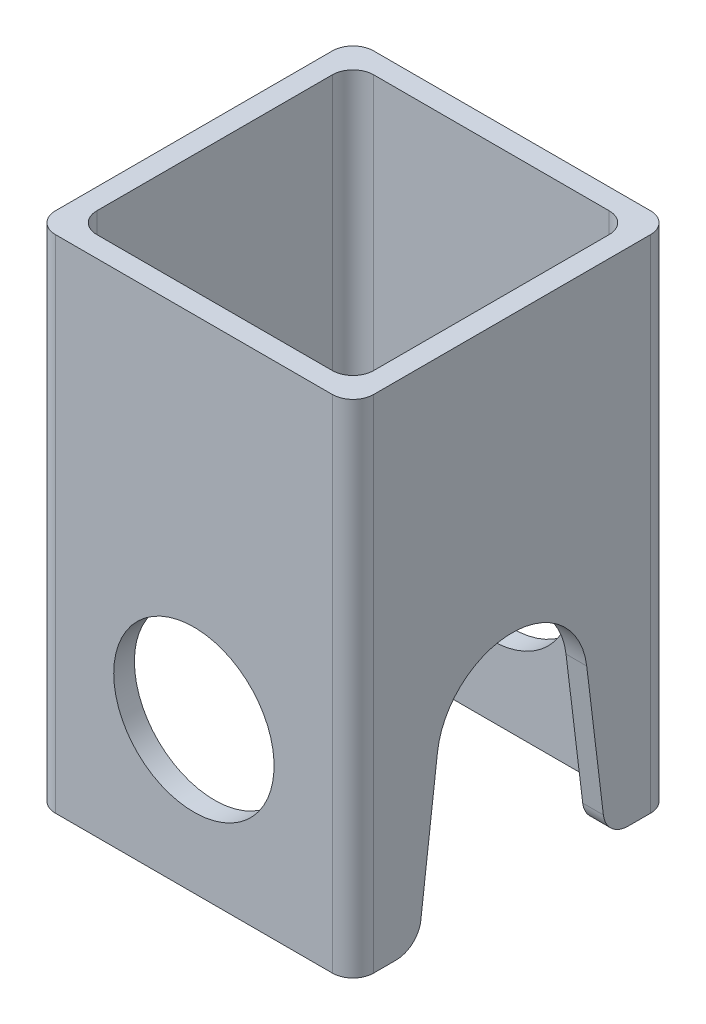
SolidWorks part; units mm, degrees
material "AISI 4130 Steel, normalized at 870C"
ref_plane "Front Plane" through (0, 0, 0) normal (0, 0, 1) x (1, 0, 0)
ref_plane "Top Plane" through (0, 0, 0) normal (0, 1, 0) x (1, 0, 0)
ref_plane "Right Plane" through (0, 0, 0) normal (1, 0, 0) x (0, 0, -1)
sketch "Sketch1" plane through (0, 0, 0) normal (1, 0, 0) x (0, 0, -1)
  line L0 (0, 0) -> (0, 40)
  dimension "D1" = 40
other "Fsae chassis MCMASTER 4130 1IN X .065IN SQUARE STOCK(1)"
ref_plane "Plane1" through (0, 0, 0) normal (0, 1, 0) x (0, 0, 1)
sketch "Sketch2" plane through (0, 0, 0) normal (0, 1, 0) x (0, 0, 1)
  line L1 (11.049, 12.7) -> (-11.049, 12.7)
  line L2 (12.7, 11.049) -> (12.7, -11.049)
  line L3 (11.049, -12.7) -> (-11.049, -12.7)
  line L4 (-12.7, 11.049) -> (-12.7, -11.049)
  line L5 (-9.398, 11.049) -> (9.398, 11.049)
  line L6 (-11.049, 9.398) -> (-11.049, -9.398)
  line L7 (-9.398, -11.049) -> (9.398, -11.049)
  line L8 (11.049, 9.398) -> (11.049, -9.398)
  arc A0 (-11.049, -12.7) -> (-12.7, -11.049) centre (-11.049, -11.049) cw
  arc A1 (12.7, -11.049) -> (11.049, -12.7) centre (11.049, -11.049) cw
  arc A2 (11.049, 12.7) -> (12.7, 11.049) centre (11.049, 11.049) cw
  arc A3 (-11.049, 12.7) -> (-12.7, 11.049) centre (-11.049, 11.049) ccw
  arc A4 (9.398, 11.049) -> (11.049, 9.398) centre (9.398, 9.398) cw
  arc A5 (11.049, -9.398) -> (9.398, -11.049) centre (9.398, -9.398) cw
  arc A6 (-9.398, -11.049) -> (-11.049, -9.398) centre (-9.398, -9.398) cw
  arc A7 (-11.049, 9.398) -> (-9.398, 11.049) centre (-9.398, 9.398) cw
  point P4 (0, -12.7)
  point P5 (12.7, 0)
  point P6 (0, 0)
  point P7 (0, 11.049)
  point P12 (12.7, -12.7)
  point P15 (12.7, 12.7)
  point P18 (-12.7, 12.7)
  point P23 (11.049, 0)
  point P24 (0, 0)
  dimension "D3" = 1.651
  dimension "D5" = 1.651
  dimension "D1" = 25.4
  dimension "D2" = 25.4
  dimension "D4" = 1.651
sketch "Sketch3" plane through (0, 0, 12.7) normal (0, 0, 1) x (1, 0, 0)
  circle A0 centre (0, 12) radius 6.4
  point P2 (0, 11.8221)
  point P4 (0, 0)
  dimension "D1" = 12.8
  dimension "D2" = 12
extrude "Cut-Extrude1" cut sketch "Sketch3" against normal through all both and the other way through all
sketch "Sketch4" plane through (12.7, 0, 0) normal (1, 0, 0) x (0, 0, -1)
  line L0 (0, 0) -> (0, 40) construction
  line L1 (-11.049, 40) -> (11.049, 40) construction
  line L2 (-7.5, 0) -> (7.5, 0)
  line L4 (-11.049, 0) -> (11.049, 0) construction
  line L5 (-5.9563, 12.7227) -> (-7.5, 0)
  line L6 (5.9563, 12.7227) -> (7.5, 0)
  arc A0 (-5.9563, 12.7227) -> (5.9563, 12.7227) centre (0, 12) cw
  point P5 (6, 12)
  point P13 (0, 0)
  dimension "D1" = 6
  dimension "D2" = 15
  dimension "D3" = 12
extrude "Cut-Extrude2" cut sketch "Sketch4" against normal through all both and the other way through all
fillet "Fillet1" radius 2 4 edges at (-11.8745, 0, -7.5) (11.8745, 0, -7.5) (11.8745, 0, 7.5) (-11.8745, 0, 7.5)
